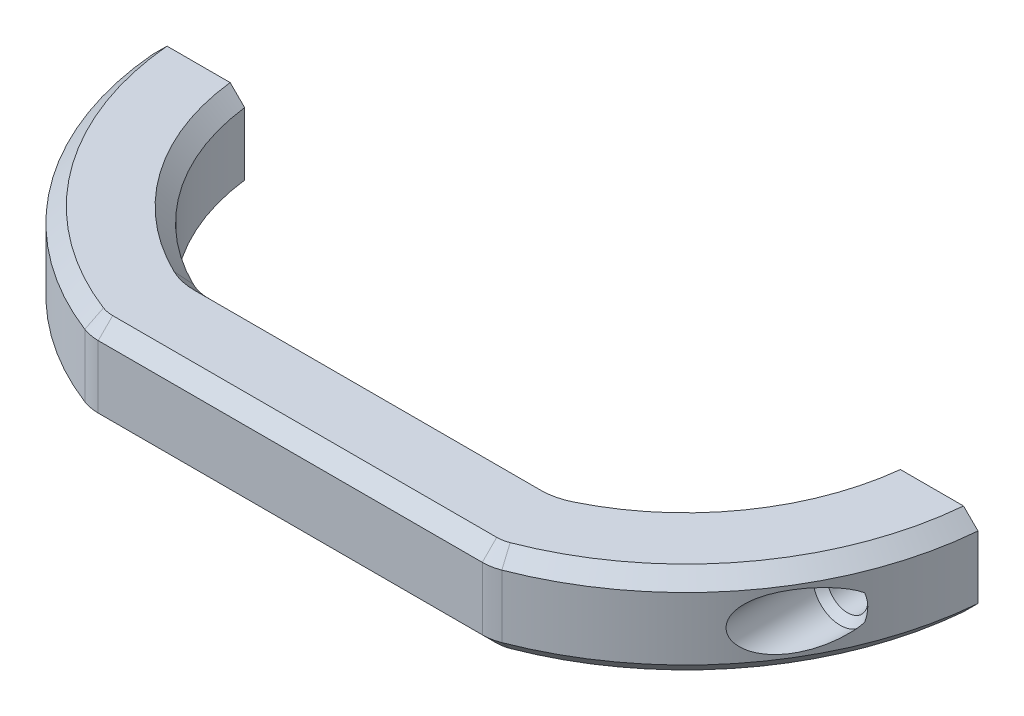
SolidWorks part; units mm, degrees
material "ABS"
ref_plane "Front Plane" through (0, 0, 0) normal (0, 0, 1) x (1, 0, 0)
ref_plane "Top Plane" through (0, 0, 0) normal (0, 1, 0) x (1, 0, 0)
ref_plane "Right Plane" through (0, 0, 0) normal (1, 0, 0) x (0, 0, -1)
sketch "Sketch2" plane through (0, 0, 0) normal (0, 1, 0) x (1, 0, 0)
  line L0 (-27.7404, -38.1) -> (27.7404, -38.1)
  line L1 (-57.1827, 0) -> (-44.4173, 0)
  line L2 (44.4173, 0) -> (57.1827, 0)
  line L3 (-25.3673, -25.4) -> (25.3673, -25.4)
  line L4 (0, -38.1) -> (0, -25.4) construction
  arc A0 (27.7404, -38.1) -> (57.1827, 0) centre (12.8952, 3.7978) ccw
  arc A1 (44.4173, 0) -> (25.3673, -25.4) centre (12.8952, 3.7978) cw
  arc A2 (-44.4173, 0) -> (-25.3673, -25.4) centre (-12.8952, 3.7978) ccw
  arc A3 (-27.7404, -38.1) -> (-57.1827, 0) centre (-12.8952, 3.7978) cw
  point P12 (-50.8, 0)
  point P13 (50.8, 0)
  point P17 (0, 0)
  point P18 (0, 0)
  point P19 (48.9337, -25.4)
  point P20 (-49.5046, -25.4)
  point P21 (50.2466, -25.4)
  dimension "D5" = 31.75
  dimension "D6" = 12.7
  dimension "D1" = 101.6
  dimension "D2" = 25.4
  dimension "D3" = 12.7
  dimension "D4" = 19.05
extrude "Boss-Extrude1" add sketch "Sketch2" along normal mid plane 12.7
fillet "Fillet1" radius 6.35 4 edges at (-25.3673, 0, 25.4) (25.3673, 0, 25.4) (27.7404, 0, 38.1) (-27.7404, 0, 38.1)
chamfer "Chamfer1" distance 2 angle 45 20 edges at (-48.4387, -6.35, 22.8942) (48.4387, -6.35, 22.8942) (-27.7674, -6.35, 37.9928) (27.7674, -6.35, 37.9928) (0, -6.35, 38.1) (38.7491, -6.35, 14.6316) (-38.7491, -6.35, 14.6316) (25.4154, -6.35, 25.2384) (-25.4154, -6.35, 25.2384) (0, -6.35, 25.4) (38.7491, 6.35, 14.6316) (-38.7491, 6.35, 14.6316) (25.4154, 6.35, 25.2384) (-25.4154, 6.35, 25.2384) (0, 6.35, 25.4) (-48.4387, 6.35, 22.8942) (48.4387, 6.35, 22.8942) (-27.7674, 6.35, 37.9928) (27.7674, 6.35, 37.9928) (0, 6.35, 38.1)
ref_plane "Plane1" through (0, 0, 12.7) normal (0, 0, 1) x (1, 0, 0)
sketch "Sketch3" plane through (0, 0, 12.7) normal (0, 0, 1) x (1, 0, 0)
  line L0 (55.175, 6.35) -> (46.4309, 6.35) construction
  line L1 (-46.4309, 6.35) -> (-55.175, 6.35) construction
  circle A0 centre (50.803, 0) radius 2.54
  circle A1 centre (-50.803, 0) radius 2.54
  point P6 (50.803, 6.35)
  point P9 (-50.803, 6.35)
  point P10 (0, 0)
  point P12 (0, 0)
  dimension "D1" = 5.08
extrude "Cut-Extrude1" cut sketch "Sketch3" along normal through all
hole_wizard "#10 Clearance Hole1" positions "Sketch4" profile "Sketch5" hole size "#10" standard "ANSI Inch"
sketch "Sketch4" plane through (0, 0, 12.7) normal (0, 0, 1) x (1, 0, 0)
  point P3 (50.803, 0)
  point P6 (-50.803, 0)
sketch "Sketch5" plane through (50.803, 0, 12.7) normal (1, 0, 0) x (0, -1, 0)
  line L0 (0, 0) -> (0, 12.7)
  line L1 (0, 12.7) -> (2.8067, 12.7)
  line L2 (2.8067, 12.7) -> (2.8067, 1.0033)
  line L3 (2.8067, 1.0033) -> (3.81, 0)
  line L5 (3.81, 0) -> (0, 0)
  line L6 (-2.8067, 1.0033) -> (-3.81, 0) construction
  line L11 (0, -6.35) -> (0, 107.95) construction
  dimension "Thru Hole Dia." = 5.6134
  dimension "Thru Hole Depth" = 12.7
  dimension "Near C'Sink Dia." = 7.62
  dimension "Near C'Sink Angle" = 90
sketch "Sketch6" plane through (0, 0, 12.7) normal (0, 0, 1) x (1, 0, 0)
  circle A0 centre (50.803, 0) radius 3.81
  arc A1 (54.1702, -1.7825) -> (54.1702, 1.7825) centre (50.803, 0) ccw construction
  circle A2 centre (-50.803, 0) radius 3.81
  arc A3 (-54.1702, 1.7825) -> (-54.1702, -1.7825) centre (-50.803, 0) ccw construction
extrude "Cut-Extrude2" cut sketch "Sketch6" along normal through all
